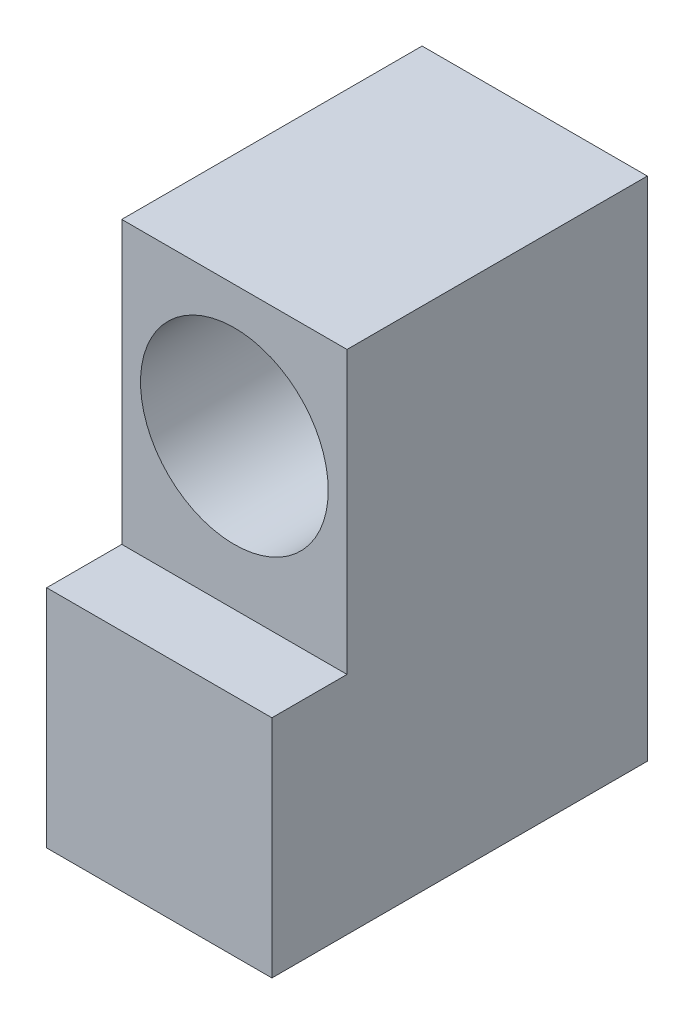
SolidWorks part; units mm, degrees
ref_plane "정면" through (0, 0, 0) normal (0, 0, 1) x (1, 0, 0)
ref_plane "윗면" through (0, 0, 0) normal (0, 1, 0) x (1, 0, 0)
ref_plane "우측면" through (0, 0, 0) normal (1, 0, 0) x (0, 0, -1)
sketch "스케치1" plane through (0, 0, 0) normal (0, 0, 1) x (1, 0, 0)
  line L0 (3, 13.5) -> (3, 0) construction
  line L1 (0, 0) -> (0.5, 0)
  line L2 (0, 0) -> (0, 13.5)
  line L3 (0, 13.5) -> (6, 13.5)
  line L4 (6, 0) -> (6, 13.5)
  line L5 (0, 6.75) -> (6, 6.75) construction
  line L6 (7.604, 0) -> (7.604, 6) construction
  line L7 (7.604, 6) -> (0, 6) construction
  line L8 (6.9826, 13) -> (6.9826, 7) construction
  line L9 (6.9826, 10) -> (-2.7621, 10) construction
  line L10 (0.5, 10) -> (0.5, -1.371) construction
  line L11 (5.5, 10) -> (5.5, -2.0709) construction
  line L12 (0.5, 0) -> (0.5, 6)
  line L13 (0.5, 6) -> (5.5, 6)
  line L14 (5.5, 6) -> (5.5, 0)
  line L15 (5.5, 0) -> (6, 0)
  circle A0 centre (3, 10) radius 2.5
extrude "돌출1" add sketch "스케치1" along normal blind 8
sketch "스케치5" plane through (0, 0, 8) normal (0, 0, 1) x (1, 0, 0)
  line L0 (0, 0) -> (0, 6.0034)
  line L1 (0, 13.5) -> (0, 0) construction
  line L2 (0, 6.0034) -> (6, 6.0034)
  line L3 (6, 0) -> (6, 13.5) construction
  line L4 (6, 6.0034) -> (6, 0)
  line L5 (6, 0) -> (0, 0)
extrude "돌출4" add sketch "스케치5" along normal blind 2
sketch "스케치6" plane through (0, 0, 8) normal (0, 0, -1) x (-1, 0, 0)
  line L0 (-0.5, 6) -> (-5.5, 6) construction
  line L1 (-5.5, 0) -> (-0.5, 0)
  line L2 (-5.5, 0) -> (-5.5, 6)
  line L3 (-5.5, 6) -> (-0.5, 6)
  line L4 (-0.5, 0) -> (-0.5, 6)
extrude "돌출5" add sketch "스케치6" along normal blind 5
hole_wizard "M2 탭을 위한 탭 드릴1" positions "스케치8" profile "스케치7" hole size "M2x0.4" standard "Ansi 미터법"
sketch "스케치8" plane through (0, 0, 0) normal (0, -1, 0) x (1, 0, 0)
  line L0 (0.0695, 10) -> (-1.6794, 10) construction
  line L1 (0, 10) -> (6, 10) construction
  line L2 (-1.6794, 10) -> (-1.6794, 7) construction
  line L7 (0, 10) -> (0, 8.4087) construction
  line L11 (3, 8.4087) -> (3, 3.6825) construction
  line L12 (-1.6794, 7) -> (7.2461, 7) construction
  point P1 (3, 7)
sketch "스케치7" plane through (3, 0, 7) normal (1, 0, 0) x (0, 0, -1)
  line L0 (0, 0) -> (0, 5.4807)
  line L1 (0, 5.4807) -> (0.8, 5)
  line L2 (0.8, 5) -> (0.8, 0)
  line L5 (0.8, 0) -> (0, 0)
  line L10 (0, 5.4807) -> (-0.8, 5) construction
  line L11 (0, -6.35) -> (0, 107.95) construction
  dimension "구멍 지름" = 1.6
  dimension "구멍 깊이" = 5
  dimension "드릴 각도" = 118
